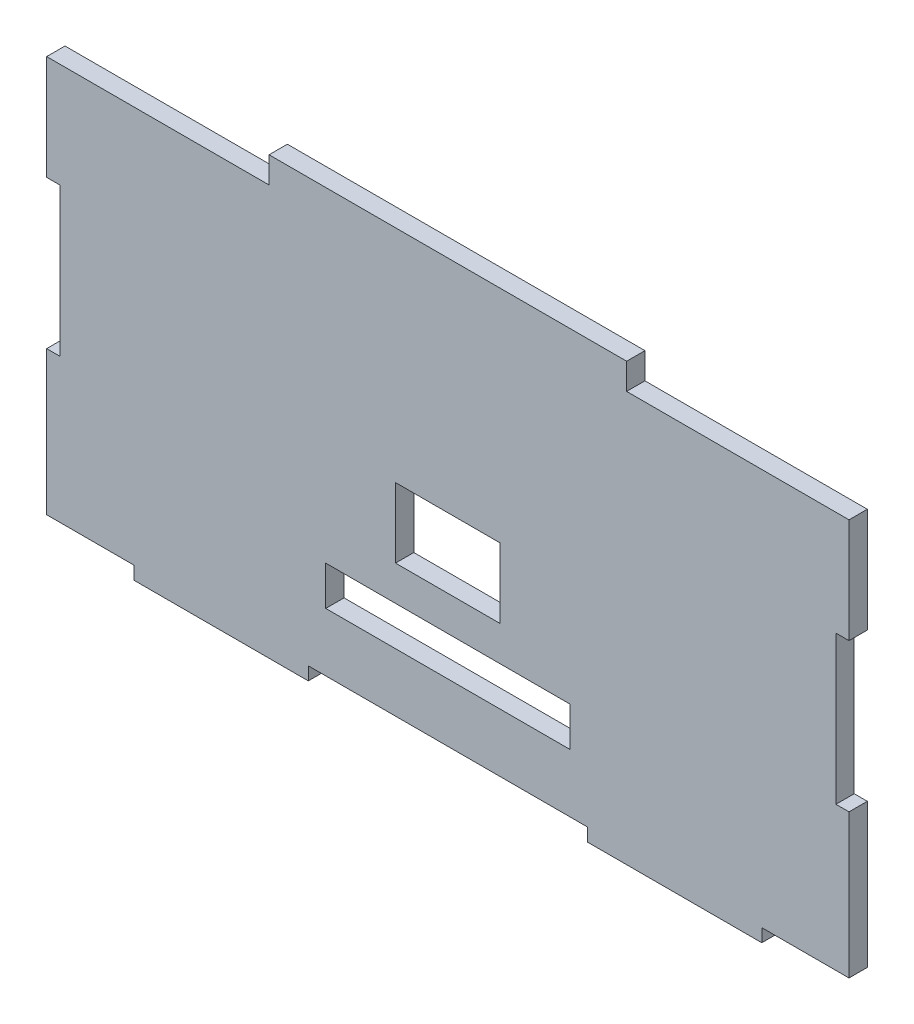
SolidWorks part; units mm, degrees
ref_plane "Front Plane" through (0, 0, 0) normal (0, 0, 1) x (1, 0, 0)
ref_plane "Top Plane" through (0, 0, 0) normal (0, 1, 0) x (1, 0, 0)
ref_plane "Right Plane" through (0, 0, 0) normal (1, 0, 0) x (0, 0, -1)
sketch "Sketch1" plane through (0, 0, 0) normal (0, 0, 1) x (1, 0, 0)
  line L0 (-46, 23.5) -> (-20.5, 23.5)
  line L1 (-46, -23.5) -> (46, -23.5)
  line L2 (-46, -23.5) -> (-46, 23.5)
  line L4 (46, -23.5) -> (46, 23.5)
  line L5 (-46, -23.5) -> (46, 23.5) construction
  line L6 (-46, 23.5) -> (46, -23.5) construction
  line L7 (-20.5, 23.5) -> (-20.5, 26.5)
  line L8 (-20.5, 26.5) -> (20.5, 26.5)
  line L9 (20.5, 26.5) -> (20.5, 23.5)
  line L10 (20.5, 23.5) -> (46, 23.5)
  point P0 (0, 0)
  dimension "D1" = 92
  dimension "D2" = 47
  dimension "D3" = 25.5
  dimension "D4" = 41
  dimension "D5" = 3
  dimension "D6" = 46
extrude "Boss-Extrude1" add sketch "Sketch1" against normal blind 2.1
sketch "Sketch2" plane through (0, 0, 0) normal (0, 0, 1) x (1, 0, 0)
  line L0 (-46, -23.5) -> (46, -23.5) construction
  line L1 (-14, -15.3) -> (14, -15.3)
  line L2 (-14, -15.3) -> (-14, -10.8)
  line L3 (-14, -10.8) -> (14, -10.8)
  line L4 (14, -15.3) -> (14, -10.8)
  line L5 (-14, -15.3) -> (14, -10.8) construction
  line L6 (-14, -10.8) -> (14, -15.3) construction
  line L7 (-46, 23.5) -> (-46, -23.5) construction
  line L8 (46, -23.5) -> (46, 23.5) construction
  line L10 (-6, -6.8) -> (6, -6.8)
  line L11 (-6, -6.8) -> (-6, 1.2)
  line L12 (-6, 1.2) -> (6, 1.2)
  line L13 (6, -6.8) -> (6, 1.2)
  line L14 (-6, -6.8) -> (6, 1.2) construction
  line L15 (-6, 1.2) -> (6, -6.8) construction
  point P0 (0, -13.05)
  point P11 (0, -2.8)
  dimension "D1" = 8.2
  dimension "D2" = 4.5
  dimension "D3" = 32
  dimension "D4" = 32
  dimension "D5" = 4
  dimension "D6" = 8
  dimension "D7" = 40
  dimension "D8" = 40
extrude "Cut-Extrude2" cut sketch "Sketch2" against normal through all
sketch "Sketch3" plane through (0, 0, 0) normal (0, 0, 1) x (1, 0, 0)
  line L0 (-46, 11.5) -> (-44.5, 11.5)
  line L1 (-46, 23.5) -> (-46, -23.5) construction
  line L2 (-44.5, 11.5) -> (-44.5, -5.5)
  line L3 (-44.5, -5.5) -> (-46, -5.5)
  line L4 (-46, -22) -> (-36, -22)
  line L5 (-36, -22) -> (-36, -23.5)
  line L6 (-46, -23.5) -> (46, -23.5) construction
  line L7 (-16, -23.5) -> (-16, -22)
  line L8 (-16, -22) -> (16, -22)
  line L9 (16, -22) -> (16, -23.5)
  line L10 (36, -23.5) -> (36, -22)
  line L11 (36, -22) -> (46, -22)
  line L12 (46, -23.5) -> (46, 23.5) construction
  line L13 (46, 11.5) -> (44.5, 11.5)
  line L14 (44.5, 11.5) -> (44.5, -5.5)
  line L15 (44.5, -5.5) -> (46, -5.5)
  line L16 (-20.5, 23.5) -> (-46, 23.5) construction
  line L17 (-46, 11.5) -> (-46, -5.5)
  line L18 (-36, -23.5) -> (-46, -23.5)
  line L19 (-46, -23.5) -> (-46, -22)
  line L20 (-16, -23.5) -> (16, -23.5)
  line L21 (36, -23.5) -> (46, -23.5)
  line L22 (46, -23.5) -> (46, -22)
  line L23 (46, -5.5) -> (46, 11.5)
  dimension "D1" = 12
  dimension "D2" = 18
  dimension "D3" = 18
  dimension "D4" = 1.5
  dimension "D5" = 1.5
  dimension "D6" = 1.5
  dimension "D7" = 1.5
  dimension "D8" = 1.5
  dimension "D9" = 10
  dimension "D10" = 10
  dimension "D11" = 30
  dimension "D12" = 30
extrude "Cut-Extrude3" cut sketch "Sketch3" against normal through all
